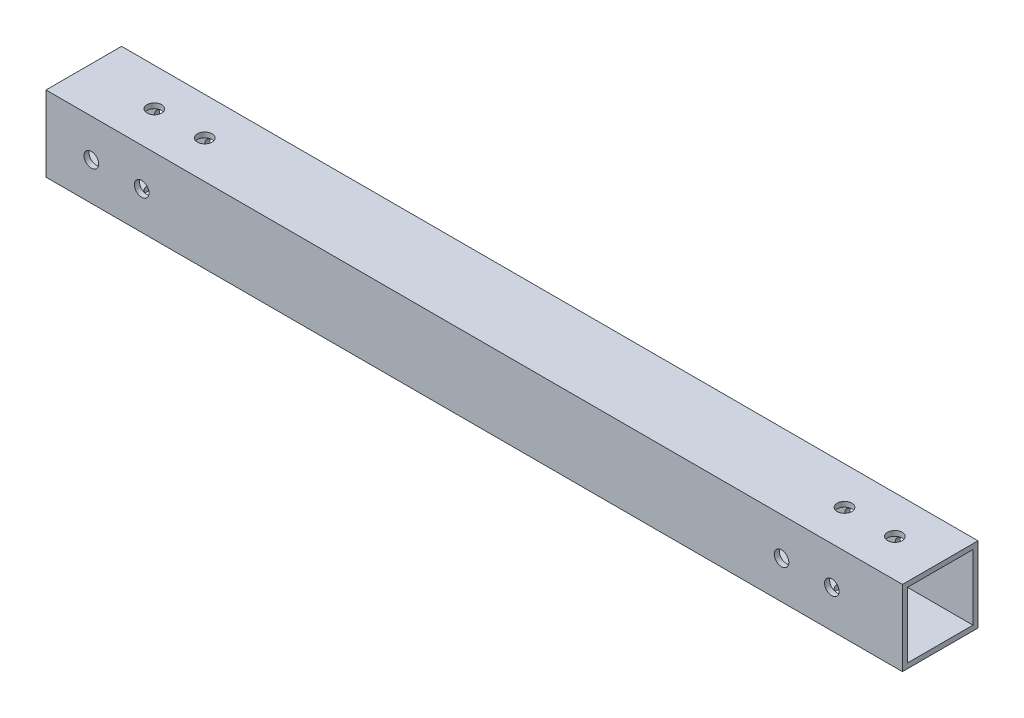
SolidWorks part; units mm, degrees
material "Thornel Mat VMA"
ref_plane "前视基准面" through (0, 0, 0) normal (0, 0, 1) x (1, 0, 0)
ref_plane "上视基准面" through (0, 0, 0) normal (0, 1, 0) x (1, 0, 0)
ref_plane "右视基准面" through (0, 0, 0) normal (1, 0, 0) x (0, 0, -1)
other "Configuration Table"
sketch "草图1" plane through (0, 0, 0) normal (1, 0, 0) x (0, 0, -1)
  line L0 (-6.5, -6.5) -> (-6.5, 6.5)
  line L1 (-7.5, -7.5) -> (7.5, -7.5)
  line L2 (-7.5, -7.5) -> (-7.5, 7.5)
  line L3 (-7.5, 7.5) -> (7.5, 7.5)
  line L4 (7.5, -7.5) -> (7.5, 7.5)
  line L5 (-7.5, -7.5) -> (7.5, 7.5) construction
  line L6 (-7.5, 7.5) -> (7.5, -7.5) construction
  line L7 (-6.5, 6.5) -> (6.5, 6.5)
  line L8 (6.5, -6.5) -> (6.5, 6.5)
  line L9 (-6.5, -6.5) -> (6.5, -6.5)
  point P0 (0, 0)
  dimension "D1" = 15
  dimension "D2" = 15
  dimension "D3" = 1
extrude "凸台-拉伸1" add sketch "草图1" along normal blind 170
sketch "草图2" plane through (0, 0, -7.5) normal (0, 0, -1) x (-1, 0, 0)
  circle A0 centre (-9, 0) radius 1.45 construction
  circle A1 centre (-19, 0) radius 1.45 construction
  circle A2 centre (-146, 0) radius 1.45 construction
  circle A3 centre (-156, 0) radius 1.45 construction
  circle A4 centre (-9, 0) radius 1.45
  circle A5 centre (-19, 0) radius 1.45
  circle A6 centre (-146, 0) radius 1.45
  circle A7 centre (-156, 0) radius 1.45
extrude "切除-拉伸1" cut sketch "草图2" against normal through all
sketch "草图3" plane through (0, 7.5, 0) normal (0, 1, 0) x (1, 0, 0)
  line L4 (0, 7.5) -> (0, -7.5)
  line L5 (0, -7.5) -> (170, -7.5)
  line L6 (170, -7.5) -> (170, 7.5)
  line L7 (170, 7.5) -> (0, 7.5)
  line L8 (0, 7.5) -> (0, -7.5)
  line L9 (0, -7.5) -> (170, -7.5)
  line L10 (170, -7.5) -> (170, 7.5)
  line L11 (170, 7.5) -> (0, 7.5)
  circle A0 centre (14, 0) radius 1.45 construction
  circle A1 centre (24, 0) radius 1.45 construction
  circle A2 centre (151, 0) radius 1.45 construction
  circle A3 centre (161, 0) radius 1.45 construction
  circle A4 centre (14, 0) radius 1.45
  circle A5 centre (24, 0) radius 1.45
  circle A6 centre (151, 0) radius 1.45
  circle A7 centre (161, 0) radius 1.45
  point P16 (0, 0)
  point P17 (0, 0)
  dimension "D1" = 0
extrude "切除-拉伸2" cut sketch "草图3" against normal through all contours A7 | A6 | A5 | A4
